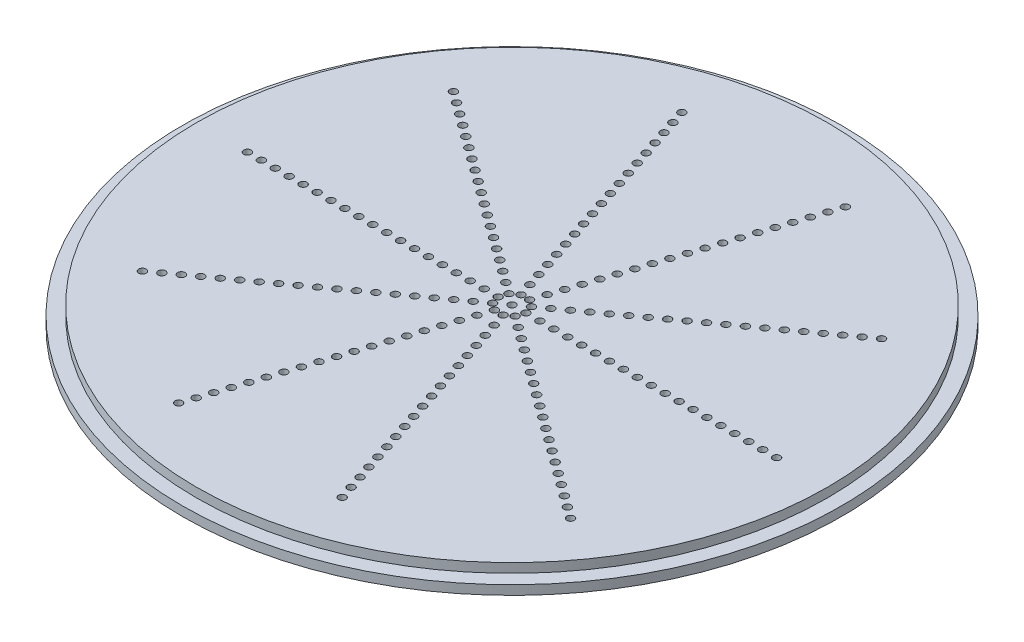
SolidWorks part; units mm, degrees
ref_plane "Front Plane" through (0, 0, 0) normal (0, 0, 1) x (1, 0, 0)
ref_plane "Top Plane" through (0, 0, 0) normal (0, 1, 0) x (1, 0, 0)
ref_plane "Right Plane" through (0, 0, 0) normal (1, 0, 0) x (0, 0, -1)
sketch "Croquis1" plane through (0, 0, 0) normal (0, 1, 0) x (1, 0, 0)
  circle A0 centre (0, 0) radius 34
  dimension "D1" = 68
extrude "Saliente-Extruir1" add sketch "Croquis1" along normal blind 1
sketch "Croquis2" plane through (0, 1, 0) normal (0, 1, 0) x (1, 0, 0)
  circle A0 centre (0, 0) radius 0.4
  circle A1 centre (1.5, 0) radius 0.4
  circle A2 centre (3, 0) radius 0.4
  circle A3 centre (4.5, 0) radius 0.4
  circle A4 centre (6, 0) radius 0.4
  circle A5 centre (7.5, 0) radius 0.4
  circle A6 centre (9, 0) radius 0.4
  circle A7 centre (10.5, 0) radius 0.4
  circle A8 centre (12, 0) radius 0.4
  circle A9 centre (13.5, 0) radius 0.4
  circle A10 centre (15, 0) radius 0.4
  circle A11 centre (16.5, 0) radius 0.4
  circle A12 centre (18, 0) radius 0.4
  circle A13 centre (19.5, 0) radius 0.4
  circle A14 centre (21, 0) radius 0.4
  circle A15 centre (22.5, 0) radius 0.4
  circle A16 centre (24, 0) radius 0.4
  circle A17 centre (25.5, 0) radius 0.4
  circle A18 centre (27, 0) radius 0.4
  circle A19 centre (28.5, 0) radius 0.4
  circle A20 centre (1.2135, -0.8817) radius 0.4
  circle A21 centre (2.4271, -1.7634) radius 0.4
  circle A22 centre (3.6406, -2.645) radius 0.4
  circle A23 centre (4.8541, -3.5267) radius 0.4
  circle A24 centre (6.0676, -4.4084) radius 0.4
  circle A25 centre (7.2812, -5.2901) radius 0.4
  circle A26 centre (8.4947, -6.1717) radius 0.4
  circle A27 centre (9.7082, -7.0534) radius 0.4
  circle A28 centre (10.9217, -7.9351) radius 0.4
  circle A29 centre (12.1353, -8.8168) radius 0.4
  circle A30 centre (13.3488, -9.6985) radius 0.4
  circle A31 centre (14.5623, -10.5801) radius 0.4
  circle A32 centre (15.7758, -11.4618) radius 0.4
  circle A33 centre (16.9894, -12.3435) radius 0.4
  circle A34 centre (18.2029, -13.2252) radius 0.4
  circle A35 centre (19.4164, -14.1068) radius 0.4
  circle A36 centre (20.6299, -14.9885) radius 0.4
  circle A37 centre (21.8435, -15.8702) radius 0.4
  circle A38 centre (23.057, -16.7519) radius 0.4
  circle A39 centre (0.4635, -1.4266) radius 0.4
  circle A40 centre (0.9271, -2.8532) radius 0.4
  circle A41 centre (1.3906, -4.2798) radius 0.4
  circle A42 centre (1.8541, -5.7063) radius 0.4
  circle A43 centre (2.3176, -7.1329) radius 0.4
  circle A44 centre (2.7812, -8.5595) radius 0.4
  circle A45 centre (3.2447, -9.9861) radius 0.4
  circle A46 centre (3.7082, -11.4127) radius 0.4
  circle A47 centre (4.1717, -12.8393) radius 0.4
  circle A48 centre (4.6353, -14.2658) radius 0.4
  circle A49 centre (5.0988, -15.6924) radius 0.4
  circle A50 centre (5.5623, -17.119) radius 0.4
  circle A51 centre (6.0258, -18.5456) radius 0.4
  circle A52 centre (6.4894, -19.9722) radius 0.4
  circle A53 centre (6.9529, -21.3988) radius 0.4
  circle A54 centre (7.4164, -22.8254) radius 0.4
  circle A55 centre (7.8799, -24.2519) radius 0.4
  circle A56 centre (8.3435, -25.6785) radius 0.4
  circle A57 centre (8.807, -27.1051) radius 0.4
  circle A58 centre (-0.4635, -1.4266) radius 0.4
  circle A59 centre (-0.9271, -2.8532) radius 0.4
  circle A60 centre (-1.3906, -4.2798) radius 0.4
  circle A61 centre (-1.8541, -5.7063) radius 0.4
  circle A62 centre (-2.3176, -7.1329) radius 0.4
  circle A63 centre (-2.7812, -8.5595) radius 0.4
  circle A64 centre (-3.2447, -9.9861) radius 0.4
  circle A65 centre (-3.7082, -11.4127) radius 0.4
  circle A66 centre (-4.1717, -12.8393) radius 0.4
  circle A67 centre (-4.6353, -14.2658) radius 0.4
  circle A68 centre (-5.0988, -15.6924) radius 0.4
  circle A69 centre (-5.5623, -17.119) radius 0.4
  circle A70 centre (-6.0258, -18.5456) radius 0.4
  circle A71 centre (-6.4894, -19.9722) radius 0.4
  circle A72 centre (-6.9529, -21.3988) radius 0.4
  circle A73 centre (-7.4164, -22.8254) radius 0.4
  circle A74 centre (-7.8799, -24.2519) radius 0.4
  circle A75 centre (-8.3435, -25.6785) radius 0.4
  circle A76 centre (-8.807, -27.1051) radius 0.4
  circle A77 centre (-1.2135, -0.8817) radius 0.4
  circle A78 centre (-2.4271, -1.7634) radius 0.4
  circle A79 centre (-3.6406, -2.645) radius 0.4
  circle A80 centre (-4.8541, -3.5267) radius 0.4
  circle A81 centre (-6.0676, -4.4084) radius 0.4
  circle A82 centre (-7.2812, -5.2901) radius 0.4
  circle A83 centre (-8.4947, -6.1717) radius 0.4
  circle A84 centre (-9.7082, -7.0534) radius 0.4
  circle A85 centre (-10.9217, -7.9351) radius 0.4
  circle A86 centre (-12.1353, -8.8168) radius 0.4
  circle A87 centre (-13.3488, -9.6985) radius 0.4
  circle A88 centre (-14.5623, -10.5801) radius 0.4
  circle A89 centre (-15.7758, -11.4618) radius 0.4
  circle A90 centre (-16.9894, -12.3435) radius 0.4
  circle A91 centre (-18.2029, -13.2252) radius 0.4
  circle A92 centre (-19.4164, -14.1068) radius 0.4
  circle A93 centre (-20.6299, -14.9885) radius 0.4
  circle A94 centre (-21.8435, -15.8702) radius 0.4
  circle A95 centre (-23.057, -16.7519) radius 0.4
  circle A96 centre (-1.5, 0) radius 0.4
  circle A97 centre (-3, 0) radius 0.4
  circle A98 centre (-4.5, 0) radius 0.4
  circle A99 centre (-6, 0) radius 0.4
  circle A100 centre (-7.5, 0) radius 0.4
  circle A101 centre (-9, 0) radius 0.4
  circle A102 centre (-10.5, 0) radius 0.4
  circle A103 centre (-12, 0) radius 0.4
  circle A104 centre (-13.5, 0) radius 0.4
  circle A105 centre (-15, 0) radius 0.4
  circle A106 centre (-16.5, 0) radius 0.4
  circle A107 centre (-18, 0) radius 0.4
  circle A108 centre (-19.5, 0) radius 0.4
  circle A109 centre (-21, 0) radius 0.4
  circle A110 centre (-22.5, 0) radius 0.4
  circle A111 centre (-24, 0) radius 0.4
  circle A112 centre (-25.5, 0) radius 0.4
  circle A113 centre (-27, 0) radius 0.4
  circle A114 centre (-28.5, 0) radius 0.4
  circle A115 centre (-1.2135, 0.8817) radius 0.4
  circle A116 centre (-2.4271, 1.7634) radius 0.4
  circle A117 centre (-3.6406, 2.645) radius 0.4
  circle A118 centre (-4.8541, 3.5267) radius 0.4
  circle A119 centre (-6.0676, 4.4084) radius 0.4
  circle A120 centre (-7.2812, 5.2901) radius 0.4
  circle A121 centre (-8.4947, 6.1717) radius 0.4
  circle A122 centre (-9.7082, 7.0534) radius 0.4
  circle A123 centre (-10.9217, 7.9351) radius 0.4
  circle A124 centre (-12.1353, 8.8168) radius 0.4
  circle A125 centre (-13.3488, 9.6985) radius 0.4
  circle A126 centre (-14.5623, 10.5801) radius 0.4
  circle A127 centre (-15.7758, 11.4618) radius 0.4
  circle A128 centre (-16.9894, 12.3435) radius 0.4
  circle A129 centre (-18.2029, 13.2252) radius 0.4
  circle A130 centre (-19.4164, 14.1068) radius 0.4
  circle A131 centre (-20.6299, 14.9885) radius 0.4
  circle A132 centre (-21.8435, 15.8702) radius 0.4
  circle A133 centre (-23.057, 16.7519) radius 0.4
  circle A134 centre (-0.4635, 1.4266) radius 0.4
  circle A135 centre (-0.9271, 2.8532) radius 0.4
  circle A136 centre (-1.3906, 4.2798) radius 0.4
  circle A137 centre (-1.8541, 5.7063) radius 0.4
  circle A138 centre (-2.3176, 7.1329) radius 0.4
  circle A139 centre (-2.7812, 8.5595) radius 0.4
  circle A140 centre (-3.2447, 9.9861) radius 0.4
  circle A141 centre (-3.7082, 11.4127) radius 0.4
  circle A142 centre (-4.1717, 12.8393) radius 0.4
  circle A143 centre (-4.6353, 14.2658) radius 0.4
  circle A144 centre (-5.0988, 15.6924) radius 0.4
  circle A145 centre (-5.5623, 17.119) radius 0.4
  circle A146 centre (-6.0258, 18.5456) radius 0.4
  circle A147 centre (-6.4894, 19.9722) radius 0.4
  circle A148 centre (-6.9529, 21.3988) radius 0.4
  circle A149 centre (-7.4164, 22.8254) radius 0.4
  circle A150 centre (-7.8799, 24.2519) radius 0.4
  circle A151 centre (-8.3435, 25.6785) radius 0.4
  circle A152 centre (-8.807, 27.1051) radius 0.4
  circle A153 centre (0.4635, 1.4266) radius 0.4
  circle A154 centre (0.9271, 2.8532) radius 0.4
  circle A155 centre (1.3906, 4.2798) radius 0.4
  circle A156 centre (1.8541, 5.7063) radius 0.4
  circle A157 centre (2.3176, 7.1329) radius 0.4
  circle A158 centre (2.7812, 8.5595) radius 0.4
  circle A159 centre (3.2447, 9.9861) radius 0.4
  circle A160 centre (3.7082, 11.4127) radius 0.4
  circle A161 centre (4.1717, 12.8393) radius 0.4
  circle A162 centre (4.6353, 14.2658) radius 0.4
  circle A163 centre (5.0988, 15.6924) radius 0.4
  circle A164 centre (5.5623, 17.119) radius 0.4
  circle A165 centre (6.0258, 18.5456) radius 0.4
  circle A166 centre (6.4894, 19.9722) radius 0.4
  circle A167 centre (6.9529, 21.3988) radius 0.4
  circle A168 centre (7.4164, 22.8254) radius 0.4
  circle A169 centre (7.8799, 24.2519) radius 0.4
  circle A170 centre (8.3435, 25.6785) radius 0.4
  circle A171 centre (8.807, 27.1051) radius 0.4
  circle A172 centre (1.2135, 0.8817) radius 0.4
  circle A173 centre (2.4271, 1.7634) radius 0.4
  circle A174 centre (3.6406, 2.645) radius 0.4
  circle A175 centre (4.8541, 3.5267) radius 0.4
  circle A176 centre (6.0676, 4.4084) radius 0.4
  circle A177 centre (7.2812, 5.2901) radius 0.4
  circle A178 centre (8.4947, 6.1717) radius 0.4
  circle A179 centre (9.7082, 7.0534) radius 0.4
  circle A180 centre (10.9217, 7.9351) radius 0.4
  circle A181 centre (12.1353, 8.8168) radius 0.4
  circle A182 centre (13.3488, 9.6985) radius 0.4
  circle A183 centre (14.5623, 10.5801) radius 0.4
  circle A184 centre (15.7758, 11.4618) radius 0.4
  circle A185 centre (16.9894, 12.3435) radius 0.4
  circle A186 centre (18.2029, 13.2252) radius 0.4
  circle A187 centre (19.4164, 14.1068) radius 0.4
  circle A188 centre (20.6299, 14.9885) radius 0.4
  circle A189 centre (21.8435, 15.8702) radius 0.4
  circle A190 centre (23.057, 16.7519) radius 0.4
  point P385 (0, 0)
  dimension "D1" = 0.8
  dimension "D2" = 20
  dimension "D3" = 10
extrude "Cortar-Extruir1" cut sketch "Croquis2" against normal through all
sketch3d "Croquis3D1"
  point P0 (14.4303, 1, -18.415)
sketch "Croquis3" plane through (0, 0, 0) normal (0, 1, 0) x (1, 0, 0)
  circle A0 centre (0, 0) radius 34
  circle A1 centre (0, 0) radius 35.5
  dimension "D1" = 71
  dimension "D2" = 68
extrude "Saliente-Extruir2" add sketch "Croquis3" against normal blind 1 separate body
